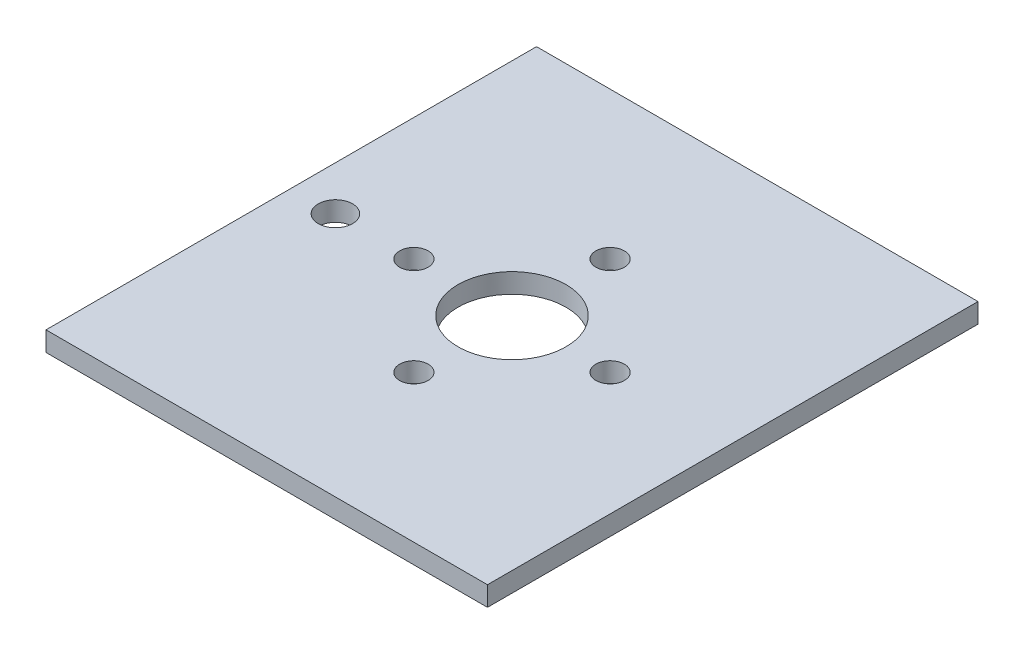
SolidWorks part; units mm, degrees
material "1.0037 (S235JR)"
ref_plane "Plan de face" through (0, 0, 0) normal (0, 0, 1) x (1, 0, 0)
ref_plane "Plan de dessus" through (0, 0, 0) normal (0, 1, 0) x (1, 0, 0)
ref_plane "Plan de droite" through (0, 0, 0) normal (1, 0, 0) x (0, 0, -1)
sketch "Esquisse1" plane through (0, 0, 0) normal (0, 1, 0) x (1, 0, 0)
  line L1 (-45, -50) -> (45, -50)
  line L2 (-45, -50) -> (-45, 50)
  line L3 (-45, 50) -> (45, 50)
  line L4 (45, -50) -> (45, 50)
  line L5 (-45, -50) -> (45, 50) construction
  line L6 (-45, 50) -> (45, -50) construction
  point P0 (0, 0)
  dimension "D1" = 90
  dimension "D2" = 100
extrude "Boss.-Extru.1" add sketch "Esquisse1" along normal blind 4
extrude "Enlèv. mat.-Extru.1" cut sketch "Esquisse2" against normal through all both and the other way through all
sketch "Esquisse2" plane through (-1346.4102, -150, 0) normal (0, 1, 0) x (0, 0, -1)
  circle A3 centre (0, -1346.4102) radius 11
hole_wizard "Dégagement M51" positions "Esquisse3" profile "Esquisse4" hole size "M5" standard "ISO"
sketch "Esquisse3" plane through (0, -8, 0) normal (0, -1, 0) x (-1, 0, 0)
  point P0 (20, 0)
  point P3 (0, -20)
  point P6 (-20, 0)
  point P9 (0, 20)
sketch "Esquisse4" plane through (-20, -8, 0) normal (1, 0, 0) x (0, 0, -1)
  line L0 (0, 0) -> (0, 21.7425)
  line L1 (0, 21.7425) -> (2.9, 20)
  line L2 (2.9, 20) -> (2.9, 0)
  line L3 (2.9, 0) -> (0, 0)
  line L4 (0, 21.7425) -> (-2.9, 20) construction
  line L5 (0, -6.35) -> (0, 107.95) construction
  dimension "Diamètre du perçage" = 5.8
  dimension "Profondeur du perçage" = 20
  dimension "Angle de pointe" = 118
hole_wizard "Dégagement M61" positions "Esquisse7" profile "Esquisse8" hole size "M6" standard "ISO"
sketch "Esquisse7" plane through (0, 0, 0) normal (0, -1, 0) x (-1, 0, 0)
  point P0 (36, 0)
sketch "Esquisse8" plane through (-36, 0, 0) normal (1, 0, 0) x (0, 0, -1)
  line L0 (0, 0) -> (0, 22.103)
  line L1 (0, 22.103) -> (3.5, 20)
  line L2 (3.5, 20) -> (3.5, 0)
  line L3 (3.5, 0) -> (0, 0)
  line L4 (0, 22.103) -> (-3.5, 20) construction
  line L5 (0, -6.35) -> (0, 107.95) construction
  dimension "Diamètre du perçage" = 7
  dimension "Profondeur du perçage" = 20
  dimension "Angle de pointe" = 118
